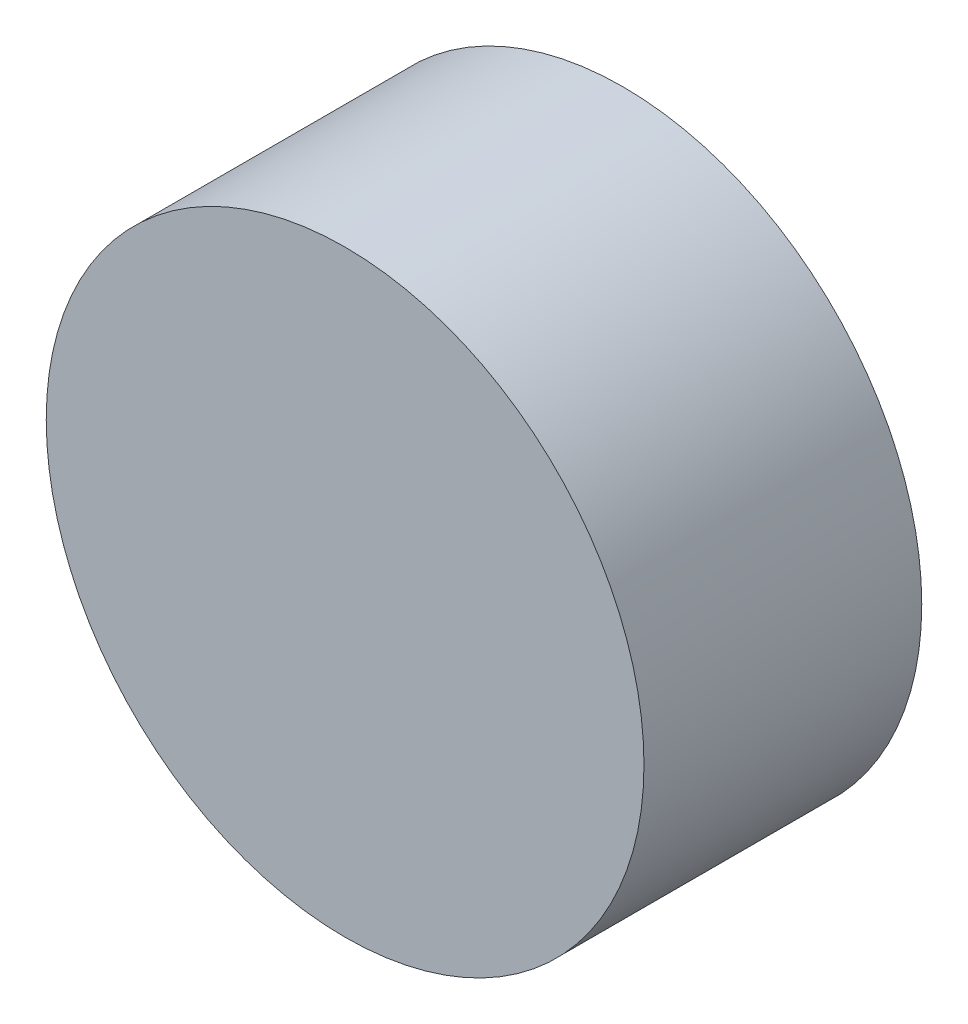
SolidWorks part; units mm, degrees
material "Polyurethane Foam Flexible"
ref_plane "Front Plane" through (0, 0, 0) normal (0, 0, 1) x (1, 0, 0)
ref_plane "Top Plane" through (0, 0, 0) normal (0, 1, 0) x (1, 0, 0)
ref_plane "Right Plane" through (0, 0, 0) normal (1, 0, 0) x (0, 0, -1)
sketch "Sketch2" plane through (0, 0, 0) normal (0, 0, 1) x (1, 0, 0)
  circle A0 centre (0, 0) radius 43.18
  dimension "D1" = 86.36
extrude "Boss-Extrude1" add sketch "Sketch2" along normal blind 40.132
equation "\"A\"= 3.4"
equation "\"D1@Sketch2\"=\"A\""
